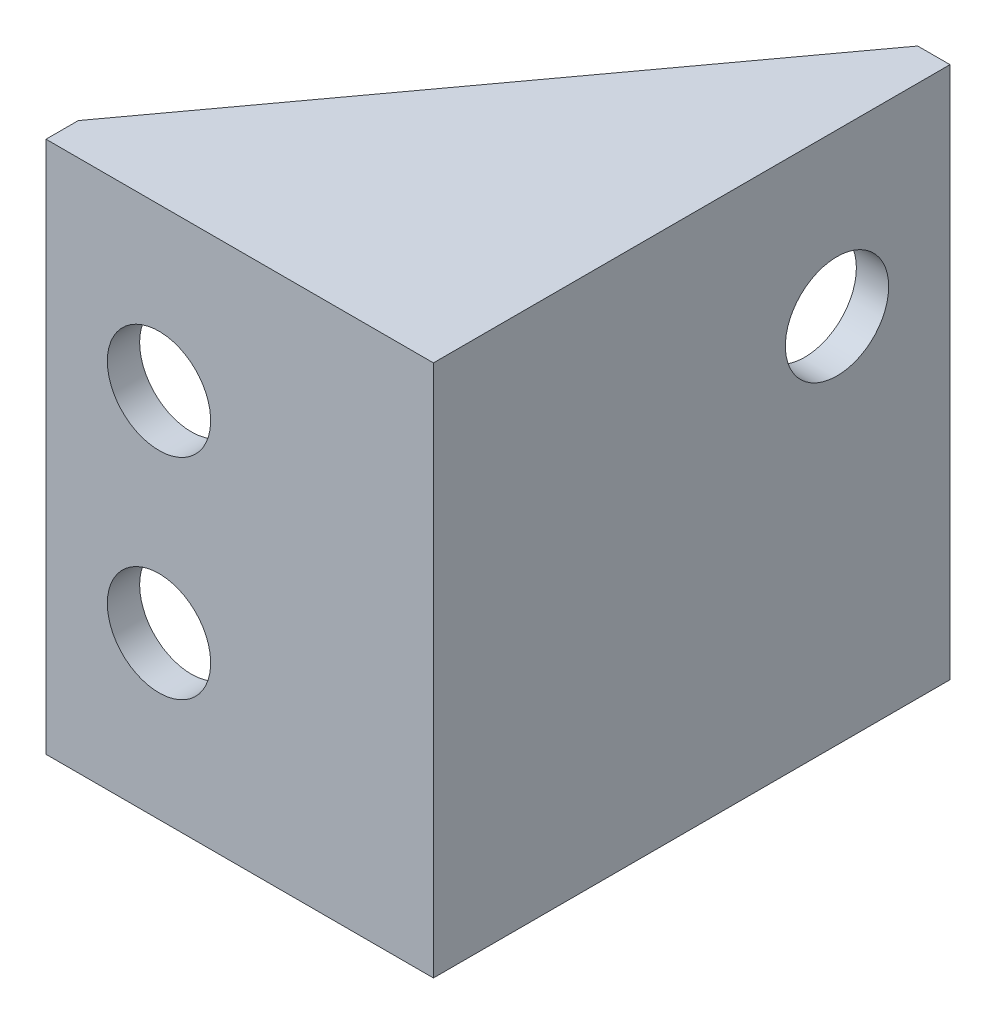
SolidWorks part; units mm, degrees
ref_plane "前视基准面" through (0, 0, 0) normal (0, 0, 1) x (1, 0, 0)
ref_plane "上视基准面" through (0, 0, 0) normal (0, 1, 0) x (1, 0, 0)
ref_plane "右视基准面" through (0, 0, 0) normal (1, 0, 0) x (0, 0, -1)
sketch "草图1" plane through (0, 0, 0) normal (0, 1, 0) x (1, 0, 0)
  line L0 (0, 0) -> (12, 0)
  line L1 (12, 0) -> (12, 16)
  line L2 (12, 16) -> (11, 16)
  line L3 (11, 16) -> (11, 1)
  line L4 (11, 1) -> (0, 1)
  line L5 (0, 1) -> (0, 0)
  dimension "D1" = 12
  dimension "D2" = 1
  dimension "D3" = 1
  dimension "D4" = 16
extrude "凸台-拉伸1" add sketch "草图1" along normal blind 16.5
sketch "草图2" plane through (12, 0, 0) normal (1, 0, 0) x (0, 0, -1)
  line L1 (0, 16.5) -> (16, 16.5) construction
  line L2 (0, 5) -> (7.0901, 5) construction
  line L3 (16, 16.5) -> (16, 0) construction
  circle A0 centre (12.5, 11.5) radius 1.6
  dimension "D1" = 3.2
  dimension "D2" = 5
  dimension "D3" = 3.5
extrude "切除-拉伸1" cut sketch "草图2" against normal blind 6
sketch "草图3" plane through (0, 0, -1) normal (0, 0, -1) x (-1, 0, 0)
  line L1 (0, 16.5) -> (0, 0) construction
  line L2 (-12, 8.25) -> (4.8779, 8.25) construction
  line L3 (-12, 16.5) -> (-12, 0) construction
  circle A0 centre (-3.5, 5) radius 1.6
  circle A1 centre (-3.5, 11.5) radius 1.6
  dimension "D2" = 3.2
  dimension "D1" = 3.5
  dimension "D4" = 6.5
extrude "切除-拉伸2" cut sketch "草图3" against normal blind 10
sketch "草图4" plane through (0, 0, 0) normal (0, -1, 0) x (1, 0, 0)
  line L0 (0, -1) -> (11, -1)
  line L1 (11, -1) -> (11, -16)
  line L2 (11, -16) -> (0, -1)
extrude "凸台-拉伸2" add sketch "草图4" against normal blind 1
sketch "草图5" plane through (0, 16.5, 0) normal (0, 1, 0) x (1, 0, 0)
  line L0 (0, 1) -> (11, 1)
  line L1 (11, 1) -> (11, 16)
  line L2 (11, 16) -> (0, 1)
extrude "凸台-拉伸3" add sketch "草图5" against normal blind 1
